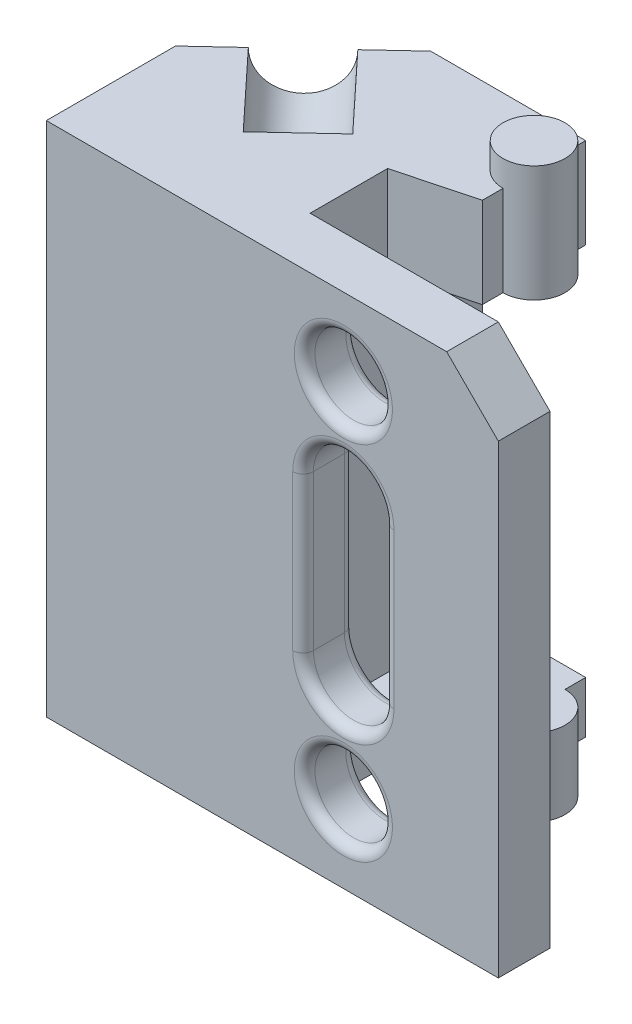
SolidWorks part; units mm, degrees
material "1060 Alloy"
ref_plane "Front Plane" through (0, 0, 0) normal (0, 0, 1) x (1, 0, 0)
ref_plane "Top Plane" through (0, 0, 0) normal (0, 1, 0) x (1, 0, 0)
ref_plane "Right Plane" through (0, 0, 0) normal (1, 0, 0) x (0, 0, -1)
sketch "Sketch1" plane through (0, 0, 0) normal (0, 1, 0) x (1, 0, 0)
  line L0 (0, 0) -> (-87.5, 0)
  line L1 (-87.5, 0) -> (-87.5, 25)
  line L2 (0, 0) -> (0, 10)
  line L3 (0, 10) -> (-46.4356, 10)
  line L5 (-61.9353, 48.8395) -> (-87.5, 25)
  line L6 (-61.9353, 48.8395) -> (-31.9353, 48.8395)
  line L8 (-31.9353, 48.8395) -> (-31.9353, 28.8395)
  line L9 (-31.9353, 28.8395) -> (-46.4356, 25)
  line L10 (-46.4356, 25) -> (-46.4356, 10)
  point P8 (-28.0884, 32.693)
  point P12 (-31.8403, 33.0341)
  point P13 (0, 0)
  dimension "D1" = 87.5
  dimension "D2" = 10
  dimension "D3" = 25
  dimension "D4" = 20
  dimension "D5" = 15
  dimension "D6" = 30
  dimension "D7" = 15
  dimension "D8" = 47
extrude "Boss-Extrude1" add sketch "Sketch1" along normal blind 100
sketch "Sketch2" plane through (0, 100, 0) normal (0, 1, 0) x (1, 0, 0)
  line L0 (-31.9353, 28.8395) -> (-31.9353, 48.8395) construction
  circle A0 centre (-31.9353, 38.8395) radius 6
extrude "Boss-Extrude2" add sketch "Sketch2" along normal blind 5 and the other way blind 105
sketch "Sketch4" plane through (-31.9353, 0, 0) normal (1, 0, 0) x (0, 0, -1)
  line L0 (44.8395, 0) -> (48.8395, 0) construction
  line L1 (54.7516, 82.5) -> (10.7452, 82.5)
  line L2 (54.7516, 82.5) -> (54.7516, 10)
  line L3 (54.7516, 10) -> (10.7452, 10)
  line L4 (10.7452, 82.5) -> (10.7452, 10)
  point P6 (46.8395, 0)
  dimension "D1" = 10
  dimension "D2" = 72.5
extrude "Cut-Extrude7" cut sketch "Sketch4" against normal blind 20 and the other way through all
sketch "Sketch5" plane through (0, 0, -10) normal (0, 0, -1) x (-1, 0, 0)
  line L0 (30, 35) -> (30, 65) construction
  line L1 (22.2012, 35) -> (22.2012, 65)
  line L2 (37.7988, 35) -> (37.7988, 65)
  line L3 (0, 0) -> (46.4356, 0) construction
  line L4 (0, 100) -> (46.4356, 100) construction
  line L5 (0, 100) -> (0, 0) construction
  circle A0 centre (30, 15) radius 7.5
  circle A1 centre (30, 85) radius 7.5
  arc A2 (22.2012, 35) -> (37.7988, 35) centre (30, 35) ccw
  arc A3 (37.7988, 65) -> (22.2012, 65) centre (30, 65) ccw
  point P6 (30, 50)
  point P13 (0, 0)
  point P16 (0, 0)
  dimension "D5" = 15
  dimension "D6" = 30
  dimension "D1" = 15
  dimension "D2" = 15
  dimension "D3" = 20
  dimension "D4" = 20
extrude "Cut-Extrude8" cut sketch "Sketch5" against normal through all
fillet "Fillet1" radius 2 12 edges at (-30, 27.2012, -10) (-22.2012, 50, -10) (-30, 72.7988, -10) (-30, 27.2012, 0) (-22.2012, 50, 0) (-30, 72.7988, 0) (-37.5, 85, 0) (-37.5, 85, -10) (-37.7988, 50, -10) (-37.7988, 50, 0) (-37.5, 15, -10) (-37.5, 15, 0)
chamfer "Chamfer1" distance 10 angle 45 1 edges at (0, 100, -5)
sketch "Sketch6" plane through (-53.1677, 0, -57.0154) normal (-0.682, 0, -0.7314) x (-0.7314, 0, 0.682)
  line L0 (11.9881, 100) -> (46.9435, 100) construction
  circle A0 centre (29.4658, 100) radius 7.5
extrude "Cut-Extrude9" cut sketch "Sketch6" against normal blind 20
equation "\"A\" = 87.5mm"
equation "\"B\"= 72.5mm"
equation "\"C\" = 47deg"
